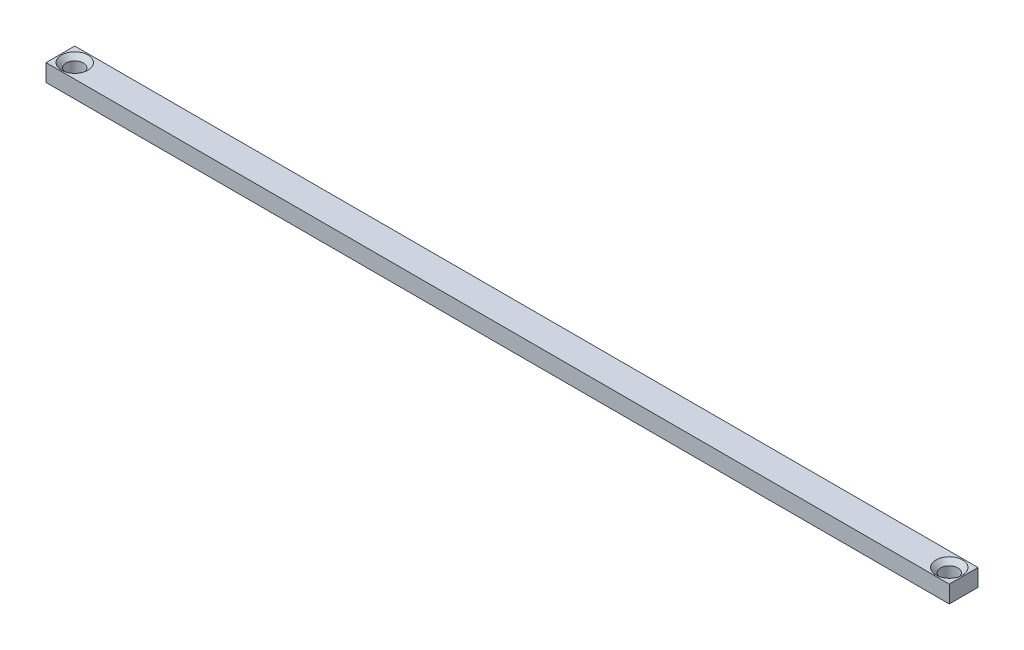
SolidWorks part; units mm, degrees
ref_plane "Front Plane" through (0, 0, 0) normal (0, 0, 1) x (1, 0, 0)
ref_plane "Top Plane" through (0, 0, 0) normal (0, 1, 0) x (1, 0, 0)
ref_plane "Right Plane" through (0, 0, 0) normal (1, 0, 0) x (0, 0, -1)
sketch "Sketch1" plane through (0, 0, 0) normal (0, 1, 0) x (1, 0, 0)
  line L0 (-139.0586, 5.3176) -> (-139.0586, 0.3176) construction
  line L1 (-141.5586, 5.3176) -> (15.6614, 5.3176)
  line L2 (-141.5586, 5.3176) -> (-141.5586, 0.3176)
  line L3 (-141.5586, 0.3176) -> (15.6614, 0.3176)
  line L4 (15.6614, 5.3176) -> (15.6614, 0.3176)
  line L5 (-141.5586, 5.3176) -> (15.6614, 0.3176) construction
  line L6 (-141.5586, 0.3176) -> (15.6614, 5.3176) construction
  line L7 (13.1614, 0.3176) -> (13.1614, 5.3176) construction
  line L8 (13.1614, 2.8176) -> (15.6614, 2.8176) construction
  line L9 (-139.0586, 2.8176) -> (-141.5586, 2.8176) construction
  circle A0 centre (13.1614, 2.8176) radius 1.5
  circle A1 centre (-139.0586, 2.8176) radius 1.5
  point P0 (-62.9486, 2.8176)
  dimension "D3" = 3
  dimension "D5" = 3
  dimension "D1" = 5
  dimension "D2" = 157.22
  dimension "D4" = 2.5
  dimension "D6" = 2.5
extrude "Boss-Extrude1" add sketch "Sketch1" along normal blind 3
chamfer "Chamfer1" distance 0.8 angle 45 2 edges at (13.1614, 3, -1.3176) (-139.0586, 3, -1.3176)
